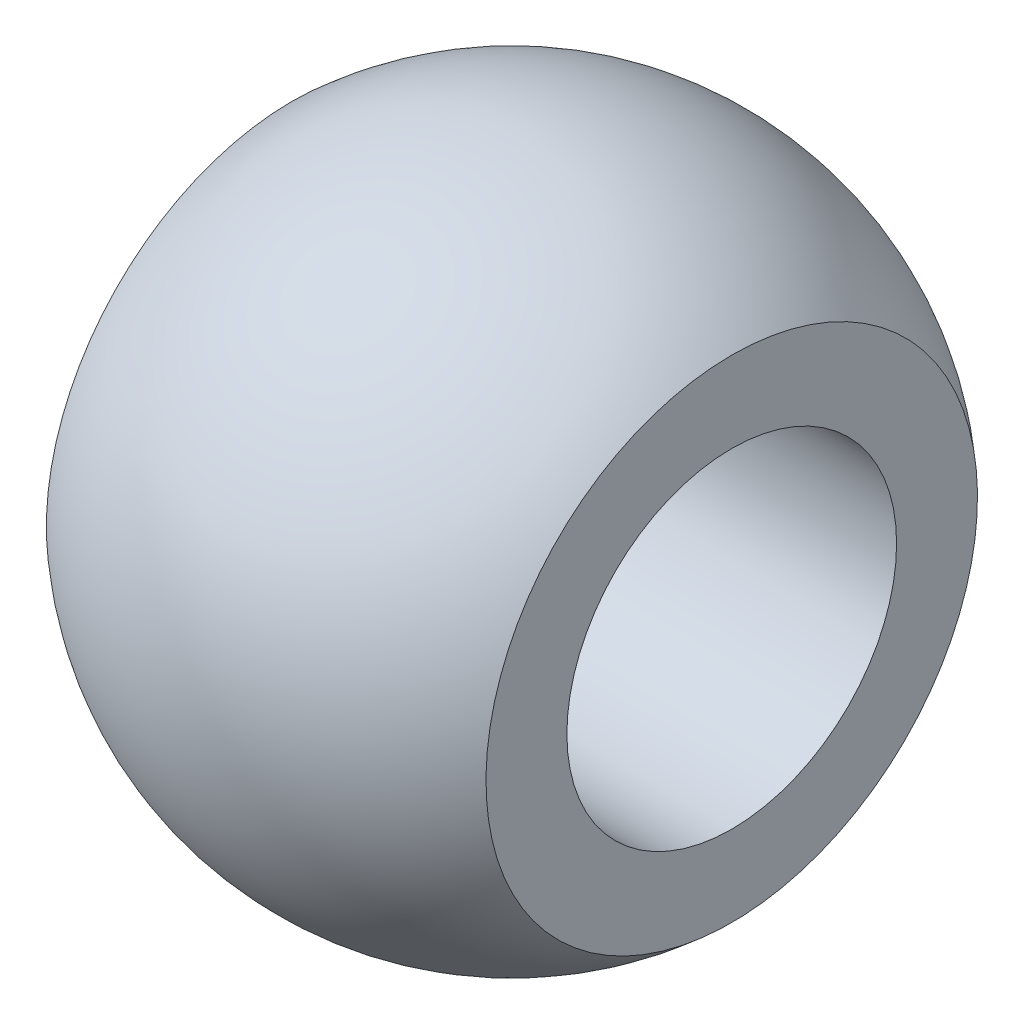
SolidWorks part; units mm, degrees
material "Chrome Stainless Steel"
ref_plane "Front Plane" through (0, 0, 0) normal (0, 0, 1) x (1, 0, 0)
ref_plane "Top Plane" through (0, 0, 0) normal (0, 1, 0) x (1, 0, 0)
ref_plane "Right Plane" through (0, 0, 0) normal (1, 0, 0) x (0, 0, -1)
sketch "Sketch1" plane through (0, 0, 0) normal (0, 0, 1) x (1, 0, 0)
  line L0 (0, 16.8126) -> (0, -18.975) construction
  line L1 (0, 12) -> (0, -12)
  arc A0 (0, 12) -> (0, -12) centre (0, 0) ccw
  dimension "D1" = 12
revolve "Revolve1" add sketch "Sketch1" angle 360 about L0
sketch "Sketch2" plane through (0, 0, 0) normal (0, 0, 1) x (1, 0, 0)
  line L1 (-8, 14.6029) -> (8, 14.6029)
  line L2 (-8, 14.6029) -> (-8, -17.8024)
  line L3 (-8, -17.8024) -> (8, -17.8024)
  line L4 (8, 14.6029) -> (8, -17.8024)
  dimension "D1" = 16
  dimension "D2" = 8
extrude "Cut-Extrude1" cut sketch "Sketch2" against normal mid plane 40 flip side to cut
sketch "Sketch3" plane through (-8, 0, 0) normal (-1, 0, 0) x (0, 0, 1)
  circle A0 centre (0, 0) radius 6
  dimension "D1" = 12
extrude "Cut-Extrude2" cut sketch "Sketch3" against normal blind 40
